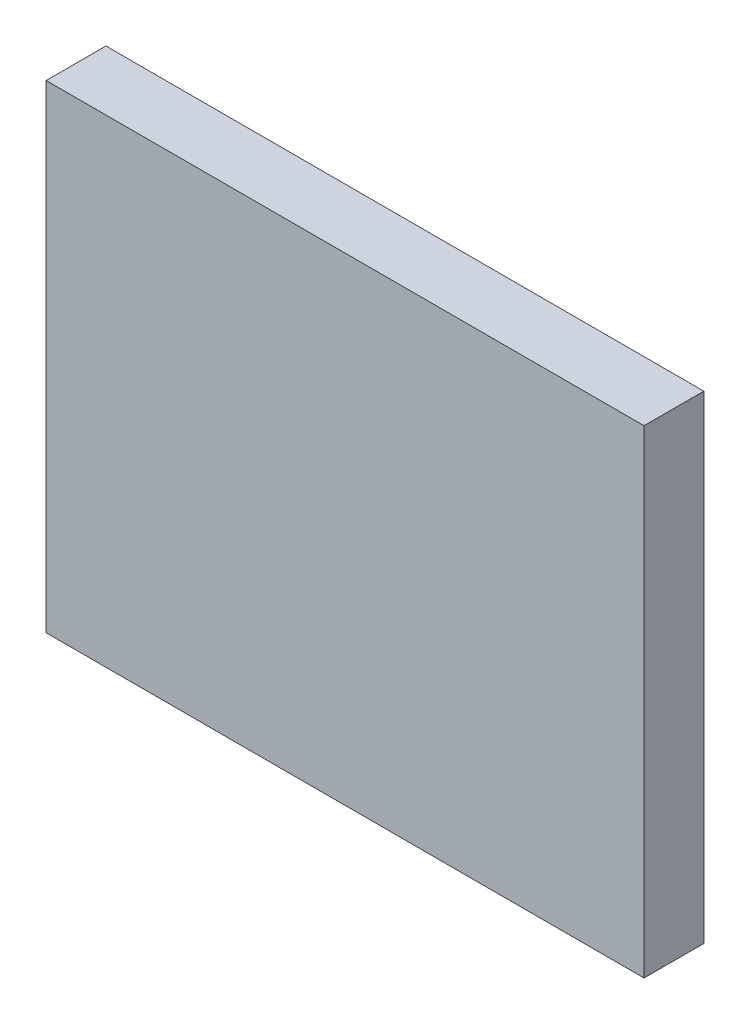
SolidWorks part; units mm, degrees
ref_plane "Front Plane" through (0, 0, 0) normal (0, 0, 1) x (1, 0, 0)
ref_plane "Top Plane" through (0, 0, 0) normal (0, 1, 0) x (1, 0, 0)
ref_plane "Right Plane" through (0, 0, 0) normal (1, 0, 0) x (0, 0, -1)
sketch "Sketch1" plane through (0, 0, 0) normal (0, 0, 1) x (1, 0, 0)
  line L0 (0, 0) -> (50, 0)
  line L1 (50, 0) -> (50, 40)
  line L2 (50, 40) -> (0, 40)
  line L3 (0, 40) -> (0, 0)
  dimension "D1" = 50
  dimension "D2" = 50
  dimension "D3" = 40
extrude "Boss-Extrude1" add sketch "Sketch1" along normal blind 5
